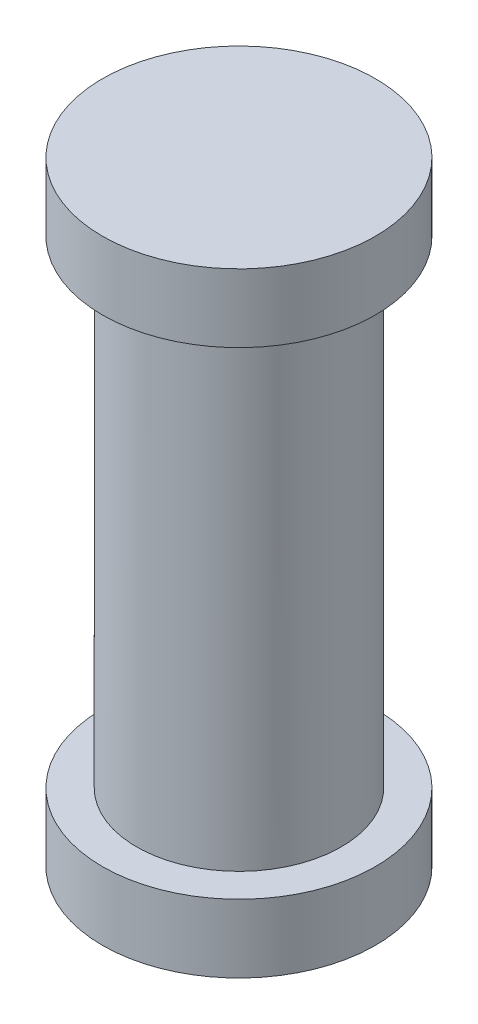
SolidWorks part; units mm, degrees
ref_plane "Front Plane" through (0, 0, 0) normal (0, 0, 1) x (1, 0, 0)
ref_plane "Top Plane" through (0, 0, 0) normal (0, 1, 0) x (1, 0, 0)
ref_plane "Right Plane" through (0, 0, 0) normal (1, 0, 0) x (0, 0, -1)
sketch "Sketch1" plane through (0, 0, 0) normal (0, 1, 0) x (1, 0, 0)
  circle A0 centre (0, 0) radius 3
  dimension "D1" = 6
extrude "Boss-Extrude1" add sketch "Sketch1" along normal mid plane 14
sketch "Sketch2" plane through (0, 7, 0) normal (0, 1, 0) x (1, 0, 0)
  circle A0 centre (0, 0) radius 4
  dimension "D1" = 8
extrude "Boss-Extrude2" add sketch "Sketch2" along normal blind 2
mirror "Mirror1" about plane through (0, 0, 0) normal (0, 1, 0) of "Boss-Extrude2"
